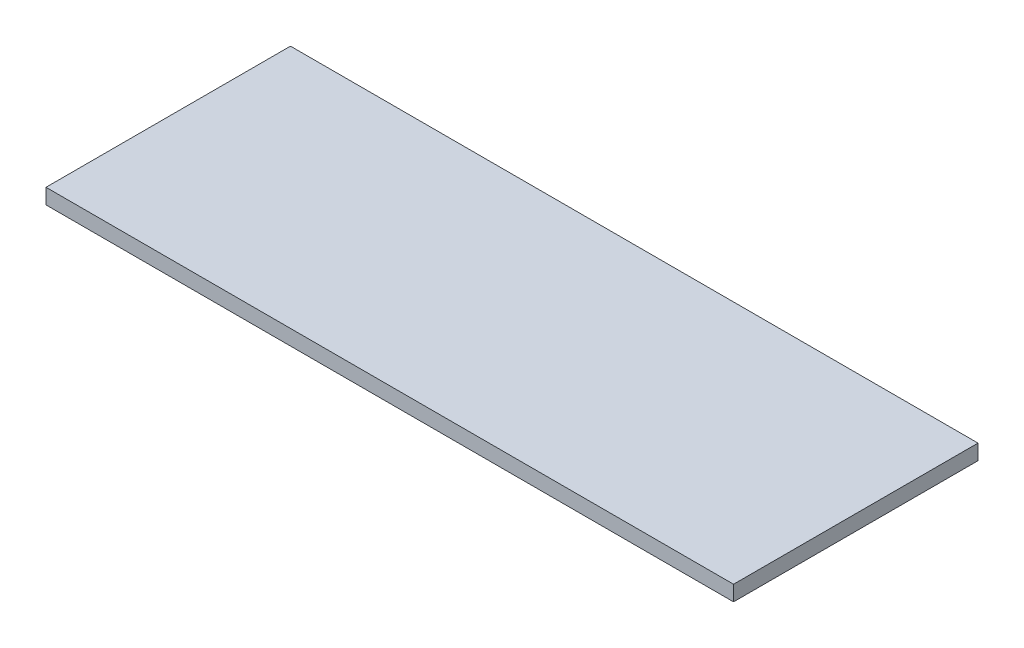
SolidWorks part; units mm, degrees
ref_plane "Front Plane" through (0, 0, 0) normal (0, 0, 1) x (1, 0, 0)
ref_plane "Top Plane" through (0, 0, 0) normal (0, 1, 0) x (1, 0, 0)
ref_plane "Right Plane" through (0, 0, 0) normal (1, 0, 0) x (0, 0, -1)
sketch "Sketch1" plane through (0, 0, 0) normal (0, 1, 0) x (1, 0, 0)
  line L1 (45, -16) -> (-45, -16)
  line L2 (45, -16) -> (45, 16)
  line L3 (45, 16) -> (-45, 16)
  line L4 (-45, -16) -> (-45, 16)
  line L5 (45, -16) -> (-45, 16) construction
  line L6 (45, 16) -> (-45, -16) construction
  point P0 (0, 0)
  dimension "D1" = 90
  dimension "D2" = 32
extrude "Boss-Extrude1" add sketch "Sketch1" along normal blind 2
